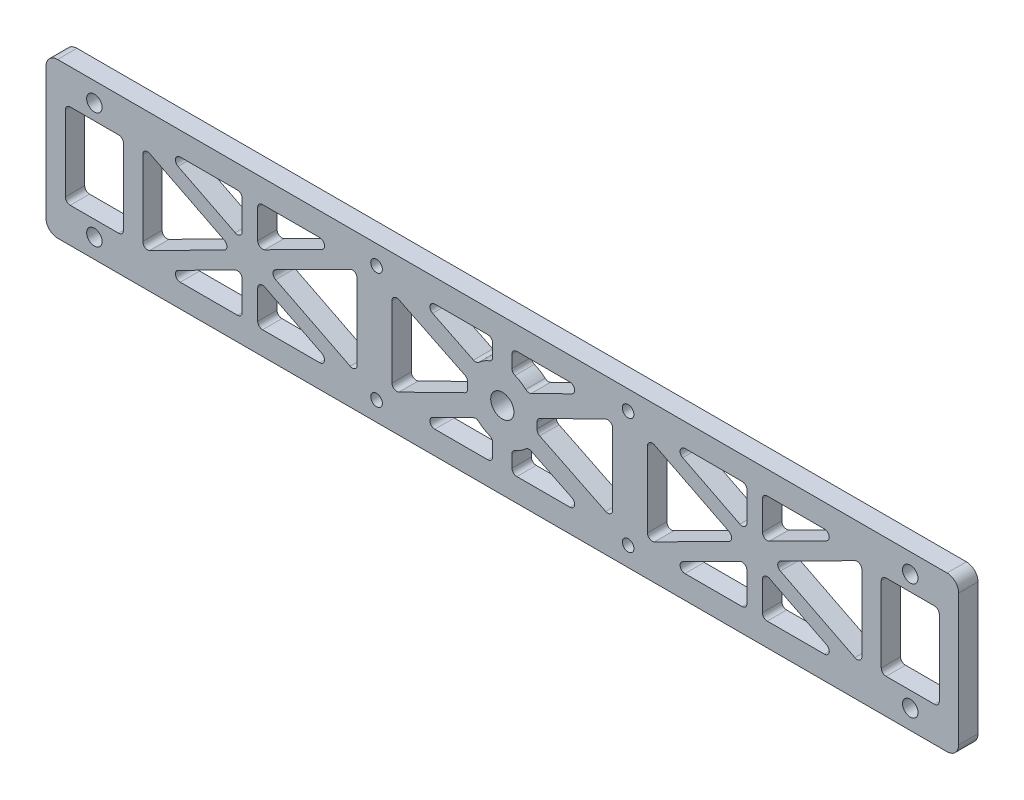
SolidWorks part; units mm, degrees
material "Thornel Mat VMA"
ref_plane "前视基准面" through (0, 0, 0) normal (0, 0, 1) x (1, 0, 0)
ref_plane "上视基准面" through (0, 0, 0) normal (0, 1, 0) x (1, 0, 0)
ref_plane "右视基准面" through (0, 0, 0) normal (1, 0, 0) x (0, 0, -1)
sketch "草图1" plane through (0, 0, 0) normal (0, 0, 1) x (1, 0, 0)
  line L1 (-117.9, -20) -> (117.9, -20)
  line L2 (-117.9, -20) -> (-117.9, 20)
  line L3 (-117.9, 20) -> (117.9, 20)
  line L4 (117.9, -20) -> (117.9, 20)
  line L5 (0, 20) -> (0, -20) construction
  line L6 (-117.9, 0) -> (117.9, 0) construction
  point P0 (0, 0)
  dimension "D1" = 235.8
  dimension "D2" = 40
extrude "凸台-拉伸1" add sketch "草图1" along normal blind 5
sketch "草图2" plane through (0, 0, 5) normal (0, 0, 1) x (1, 0, 0)
  circle A0 centre (0, 0) radius 3
  dimension "D1" = 6
extrude "切除-拉伸1" cut sketch "草图2" against normal blind 10
fillet "圆角1" radius 3 4 edges at (117.9, -20, 2.5) (117.9, 20, 2.5) (-117.9, -20, 2.5) (-117.9, 20, 2.5)
sketch "草图3" plane through (0, 0, 0) normal (0, 0, -1) x (-1, 0, 0)
  line L0 (0, 0) -> (0, 54.8319) construction
  circle A0 centre (-32.5, -15) radius 1.5 construction
  circle A1 centre (-32.5, 15) radius 1.5 construction
  circle A2 centre (-32.5, -15) radius 1.5
  circle A3 centre (-32.5, 15) radius 1.5
  circle A4 centre (32.5, 15) radius 1.5
  circle A5 centre (32.5, -15) radius 1.5
extrude "切除-拉伸2" cut sketch "草图3" against normal up to surface (5 mm away) up to face at (3, 0, 5)
sketch "草图5" plane through (0, 0, 0) normal (0, 0, -1) x (-1, 0, 0)
  line L0 (0, 0) -> (0, 55.8788) construction
  circle A0 centre (-105.4, -15) radius 2 construction
  circle A1 centre (-105.4, 15) radius 2 construction
  circle A2 centre (-105.4, -15) radius 2
  circle A3 centre (-105.4, 15) radius 2
  circle A4 centre (105.4, 15) radius 2
  circle A5 centre (105.4, -15) radius 2
extrude "切除-拉伸3" cut sketch "草图5" against normal up to surface (5 mm away) up to face at (-34, -15, 5)
sketch "草图6" plane through (0, 0, 0) normal (0, 0, -1) x (-1, 0, 0)
  line L0 (-117.9, -17) -> (-117.9, 17) construction
  line L1 (-92.9, -14) -> (-37.5, -14)
  line L2 (-92.9, -14) -> (-92.9, 14)
  line L3 (-92.9, 14) -> (-37.5, 14)
  line L4 (-37.5, -14) -> (-37.5, 14)
  line L5 (-65.2, 14) -> (-65.2, -14) construction
  line L6 (-92.9, 0) -> (-37.5, 0) construction
  line L7 (-114.9, 20) -> (114.9, 20) construction
  circle A0 centre (-32.5, 15) radius 1.5 construction
  point P0 (-65.2, 0)
  dimension "D1" = 5
  dimension "D2" = 25
  dimension "D3" = 6
extrude "切除-拉伸4" cut sketch "草图6" against normal up to surface (5 mm away) up to face at (-107.4, -15, 5)
sketch "草图7" plane through (0, 0, 0) normal (0, 0, -1) x (-1, 0, 0)
  line L0 (-92.9, 14) -> (-37.5, -14) construction
  line L1 (-92.9, -14) -> (-37.5, 14) construction
  line L2 (-65.2, 14) -> (-65.2, -14) construction
  line L3 (-37.5, 14) -> (-92.9, 14) construction
  line L4 (-92.9, -14) -> (-37.5, -14) construction
  line L5 (-93.8022, 12.215) -> (-69.6338, 0)
  line L6 (-91.9978, -15.785) -> (-67.2, -3.2518)
  line L7 (-67.2, 14) -> (-67.2, 3.2518)
  line L8 (-91.9978, 15.785) -> (-67.2, 3.2518)
  line L9 (-93.8022, -12.215) -> (-69.6338, 0)
  line L10 (-63.2, 14) -> (-63.2, 3.2518)
  line L11 (-93.8022, 12.215) -> (-91.9978, 15.785)
  line L12 (-38.4022, -15.785) -> (-36.5978, -12.215)
  line L13 (-91.9978, -15.785) -> (-93.8022, -12.215)
  line L14 (-36.5978, 12.215) -> (-38.4022, 15.785)
  line L15 (-67.2, 14) -> (-63.2, 14)
  line L16 (-67.2, -14) -> (-63.2, -14)
  line L18 (-93.8022, 12.215) -> (-38.4022, -15.785) construction
  line L20 (-93.8022, -12.215) -> (-38.4022, 15.785) construction
  line L22 (-67.2, 14) -> (-67.2, -14) construction
  line L23 (-63.2, 3.2518) -> (-38.4022, 15.785)
  line L24 (-91.9978, 15.785) -> (-36.5978, -12.215) construction
  line L25 (-63.2, -3.2518) -> (-38.4022, -15.785)
  line L26 (-67.2, -3.2518) -> (-67.2, -14)
  line L28 (-91.9978, -15.785) -> (-36.5978, 12.215) construction
  line L29 (-63.2, -3.2518) -> (-63.2, -14)
  line L30 (-63.2, 14) -> (-63.2, -14) construction
  line L31 (-60.7662, 0) -> (-36.5978, 12.215)
  line L33 (-60.7662, 0) -> (-36.5978, -12.215)
  dimension "D1" = 2
  dimension "D2" = 2
extrude "凸台-拉伸2" add sketch "草图7" against normal up to surface (5 mm away) up to face at (65.2, 0, 5)
mirror "镜向1" about plane through (0, 0, 0) normal (1, 0, 0) of "凸台-拉伸2", "切除-拉伸4"
sketch "草图8" plane through (0, 0, 0) normal (0, 0, -1) x (-1, 0, 0)
  line L0 (-117.9, -17) -> (-117.9, 17) construction
  line L1 (-112.9, -11) -> (-97.9, -11)
  line L2 (-112.9, -11) -> (-112.9, 11)
  line L3 (-112.9, 11) -> (-97.9, 11)
  line L4 (-97.9, -11) -> (-97.9, 11)
  line L5 (-105.4, 11) -> (-105.4, -11) construction
  line L6 (-112.9, 0) -> (-97.9, 0) construction
  line L7 (-92.9, 11.7591) -> (-92.9, -11.7591) construction
  line L8 (-97.9, 0) -> (0, 0) construction
  circle A0 centre (-105.4, -15) radius 2 construction
  point P0 (-105.4, 0)
  dimension "D1" = 5
  dimension "D2" = 5
  dimension "D3" = 4
extrude "切除-拉伸5" cut sketch "草图8" against normal up to surface (5 mm away) up to face at (-56.1113, 10.4173, 5)
mirror "镜向2" about plane through (0, 0, 0) normal (1, 0, 0) of "切除-拉伸5"
sketch "草图9" plane through (0, 0, 0) normal (0, 0, -1) x (-1, 0, 0)
  line L0 (-41.9338, 14) -> (-63.2, 14) construction
  line L1 (-28.5, -14) -> (28.5, -14)
  line L2 (-28.5, -14) -> (-28.5, 14)
  line L3 (-28.5, 14) -> (28.5, 14)
  line L4 (28.5, -14) -> (28.5, 14)
  line L5 (0, 14) -> (0, -14) construction
  line L6 (-28.5, 0) -> (28.5, 0) construction
  circle A0 centre (0, 0) radius 9
  circle A1 centre (32.5, 15) radius 1.5 construction
  dimension "D1" = 18
  dimension "D2" = 4
extrude "切除-拉伸6" cut sketch "草图9" against normal up to surface (5 mm away) up to face at (56.1113, 10.4173, 5)
sketch "草图10" plane through (0, 0, 0) normal (0, 0, -1) x (-1, 0, 0)
  line L0 (28.5, 14) -> (-28.5, 14) construction
  line L1 (-2.5, -14) -> (2.5, -14)
  line L2 (-2.5, -14) -> (-2.5, 14)
  line L3 (-2.5, 14) -> (2.5, 14)
  line L4 (2.5, -14) -> (2.5, 14)
  line L5 (0, 14) -> (0, -14) construction
  line L6 (-2.5, 0) -> (2.5, 0) construction
  circle A0 centre (0, 0) radius 9 construction
  circle A1 centre (0, 0) radius 9
  point P0 (0, 0)
  dimension "D1" = 5
extrude "凸台-拉伸3" add sketch "草图10" against normal up to surface (5 mm away) contours A1 L4 L3 L2 | A1 L2 L1 L4 up to face at (3, 0, 5)
sketch "草图11" plane through (0, 0, 0) normal (0, 0, -1) x (-1, 0, 0)
  line L0 (-28.5, 14) -> (28.5, -14) construction
  line L1 (-28.5, -14) -> (28.5, 14) construction
  line L2 (-29.6023, 11.7561) -> (27.3977, -16.2439)
  line L3 (-27.3977, -16.2439) -> (29.6023, 11.7561)
  line L4 (-27.3977, 16.2439) -> (29.6023, -11.7561)
  line L5 (-29.6023, -11.7561) -> (27.3977, 16.2439)
  line L6 (-29.6023, 11.7561) -> (-27.3977, 16.2439)
  line L7 (27.3977, -16.2439) -> (29.6023, -11.7561)
  line L8 (-27.3977, -16.2439) -> (-29.6023, -11.7561)
  line L9 (29.6023, 11.7561) -> (27.3977, 16.2439)
  circle A0 centre (0, 0) radius 9
  arc A1 (2.5, -8.6458) -> (2.5, 8.6458) centre (0, 0) ccw construction
  dimension "D1" = 2.5
  dimension "D2" = 2.5
extrude "凸台-拉伸4" add sketch "草图11" against normal up to surface (5 mm away) contours A0 L4 L6 L2 | A0 L5 L8 L3 | A0 L2 L7 L4 | A0 L3 L9 L5 up to face at (12.25, 0, 5)
fillet "圆角2" radius 1.25 68 edges at (-2.5, -14, 2.5) (-2.5, 8.6458, 2.5) (-2.5, -8.6458, 2.5) (8.8623, 1.5681, 2.5) (-6.6578, -6.0559, 2.5) (-22.8298, -14, 2.5) (-97.9, 11, 2.5) (-112.9, 11, 2.5) (112.9, -11, 2.5) (112.9, 11, 2.5) (97.9, 11, 2.5) (97.9, -11, 2.5) (-63.2, 14, 2.5) (-63.2, 3.2518, 2.5) (-41.9338, 14, 2.5) (-37.5, 11.7591, 2.5) (-60.7662, 0, 2.5) (-37.5, -11.7591, 2.5) (-67.2, -14, 2.5) (-67.2, -3.2518, 2.5) (-88.4662, -14, 2.5) (-92.9, -11.7591, 2.5) (-69.6338, 0, 2.5) (-92.9, 11.7591, 2.5) (-67.2, 3.2518, 2.5) (-67.2, 14, 2.5) (-88.4662, 14, 2.5) (-41.9338, -14, 2.5) (-63.2, -3.2518, 2.5) (-63.2, -14, 2.5) (63.2, -14, 2.5) (63.2, -3.2518, 2.5) (41.9338, -14, 2.5) (67.2, 14, 2.5) (67.2, 3.2518, 2.5) (88.4662, 14, 2.5) (69.6338, 0, 2.5) (92.9, -11.7591, 2.5) (92.9, 11.7591, 2.5) (67.2, -3.2518, 2.5) (67.2, -14, 2.5) (88.4662, -14, 2.5) (60.7662, 0, 2.5) (37.5, 11.7591, 2.5) (37.5, -11.7591, 2.5) (63.2, 3.2518, 2.5) (63.2, 14, 2.5) (41.9338, 14, 2.5) (2.5, 14, 2.5) (2.5, 8.6458, 2.5) (2.5, -8.6458, 2.5) (6.6578, 6.0559, 2.5) (-8.8623, -1.5681, 2.5) (22.8298, 14, 2.5) (6.6578, -6.0559, 2.5) (-8.8623, 1.5681, 2.5) (2.5, -14, 2.5) (22.8298, -14, 2.5) (28.5, 11.2147, 2.5) (8.8623, -1.5681, 2.5) (-6.6578, 6.0559, 2.5) (28.5, -11.2147, 2.5) (-2.5, 14, 2.5) (-22.8298, 14, 2.5) (-28.5, -11.2147, 2.5) (-28.5, 11.2147, 2.5) (-112.9, -11, 2.5) (-97.9, -11, 2.5)
equation "\"D1@草图7\"=\"D2@草图7\""
equation "\"D2@草图8\"= \"D1@草图8\""
